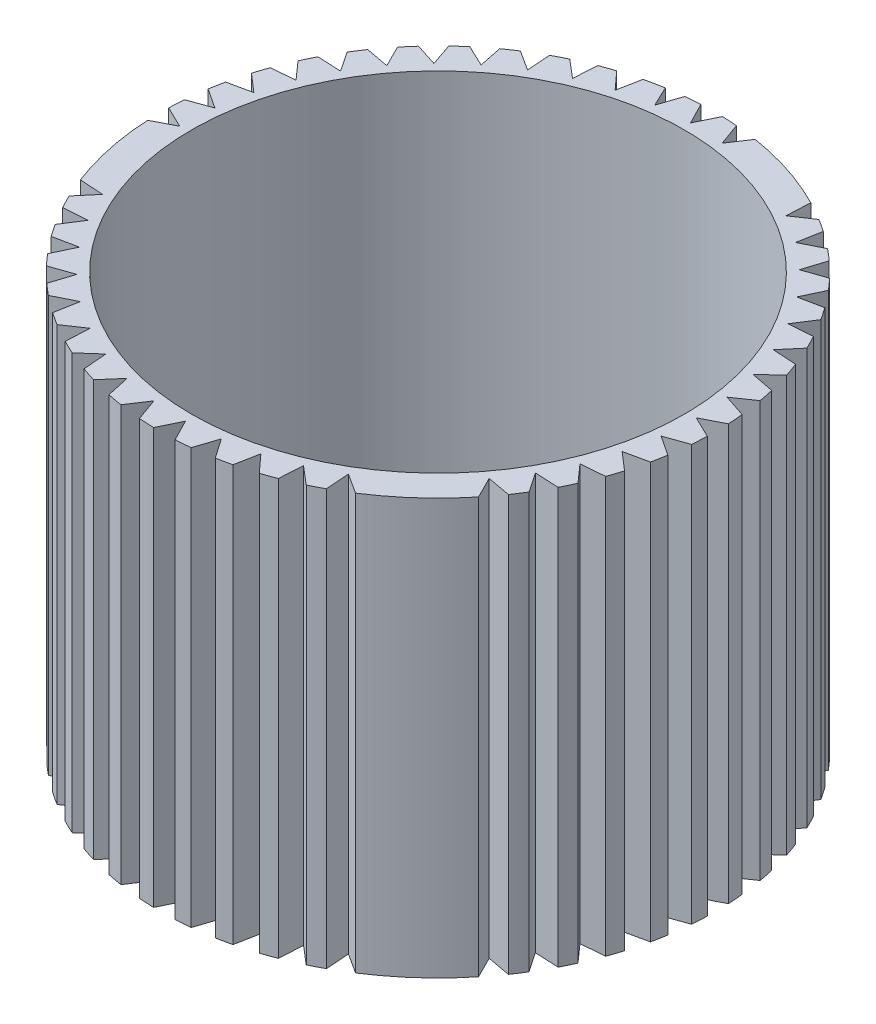
SolidWorks part; units mm, degrees
material "VeroWhite Plus"
ref_plane "Front Plane" through (0, 0, 0) normal (0, 0, 1) x (1, 0, 0)
ref_plane "Top Plane" through (0, 0, 0) normal (0, 1, 0) x (1, 0, 0)
ref_plane "Right Plane" through (0, 0, 0) normal (1, 0, 0) x (0, 0, -1)
sketch "Sketch1" plane through (0, 0, 0) normal (0, 1, 0) x (1, 0, 0)
  line L0 (9.9132, 31.394) -> (7.112, 32.1446) construction
  line L1 (11.113, 31.0725) -> (5.9121, 32.4661) construction
  line L2 (8.5126, 31.7693) -> (0, 0) construction
  line L3 (0, 0) -> (-6.2397, 29.8549) construction
  line L4 (0, 0) -> (-5.194, 30.0545) construction
  line L5 (0, 0) -> (-4.3196, 30.1926) construction
  line L6 (-4.9343, 30.0982) -> (-4.1426, 28.9552) construction
  line L7 (-4.1426, 28.9552) -> (-3.7032, 30.2744) construction
  line L8 (5.9121, 32.4661) -> (4.002, 25.3375) construction
  line L9 (11.113, 31.0725) -> (9.4356, 24.8123) construction
  line L10 (-32.4661, -5.9121) -> (-31.0725, -11.113) construction
  line L11 (-32.1446, -7.112) -> (-31.394, -9.9131) construction
  line L12 (22.2314, -24.282) -> (24.282, -22.2314) construction
  line L13 (-31.7693, -8.5126) -> (0, 0) construction
  line L14 (0, 0) -> (23.2567, -23.2567) construction
  line L15 (25.1604, -21.3531) -> (18.9649, -15.1575) construction
  line L16 (21.3531, -25.1604) -> (14.6891, -18.4964) construction
  line L17 (-32.4661, -5.9121) -> (-24.142, -3.6817) construction
  line L18 (-31.0725, -11.113) -> (-21.737, -8.6116) construction
  line L19 (-0.9635, 30.4848) -> (-0.3278, 29.2482) construction
  line L20 (-0.3278, 29.2482) -> (0.2801, 30.4987) construction
  line L21 (3.0238, 30.3497) -> (3.4927, 29.0407) construction
  line L22 (3.4927, 29.0407) -> (4.2586, 30.2012) construction
  line L23 (14.408, 26.8823) -> (14.3402, 25.4935) construction
  line L24 (14.3402, 25.4935) -> (15.4919, 26.2726) construction
  line L25 (17.7936, 24.7717) -> (17.5451, 23.4037) construction
  line L26 (17.5451, 23.4037) -> (18.7887, 24.0257) construction
  line L27 (20.8747, 22.2373) -> (20.4498, 20.9133) construction
  line L28 (20.4498, 20.9133) -> (21.7639, 21.3678) construction
  line L29 (23.5987, 19.3223) -> (23.0046, 18.0652) construction
  line L30 (23.0046, 18.0652) -> (24.3668, 18.3442) construction
  line L31 (25.9189, 16.0768) -> (25.1658, 14.9079) construction
  line L32 (25.1658, 14.9079) -> (26.5527, 15.0068) construction
  line L33 (27.7956, 12.5562) -> (26.8964, 11.4956) construction
  line L34 (26.8964, 11.4956) -> (28.2843, 11.4126) construction
  line L35 (29.1967, 8.8207) -> (28.1667, 7.8866) construction
  line L36 (28.1667, 7.8866) -> (29.532, 7.6231) construction
  line L37 (30.0982, 4.9343) -> (28.9552, 4.1426) construction
  line L38 (28.9552, 4.1426) -> (30.2744, 3.7032) construction
  line L39 (30.4848, 0.9635) -> (29.2482, 0.3278) construction
  line L40 (29.2482, 0.3278) -> (30.4987, -0.2801) construction
  line L41 (30.3497, -3.0238) -> (29.0407, -3.4927) construction
  line L42 (29.0407, -3.4927) -> (30.2012, -4.2586) construction
  line L43 (29.6954, -6.9594) -> (28.3364, -7.2534) construction
  line L44 (28.3364, -7.2534) -> (29.387, -8.1642) construction
  line L45 (28.533, -10.7759) -> (27.1472, -10.89) construction
  line L46 (27.1472, -10.89) -> (28.07, -11.9301) construction
  line L47 (26.8823, -14.408) -> (25.4935, -14.3402) construction
  line L48 (25.4935, -14.3402) -> (26.2726, -15.4919) construction
  line L49 (24.7717, -17.7936) -> (23.4037, -17.5451) construction
  line L50 (23.4037, -17.5451) -> (24.0257, -18.7887) construction
  line L51 (16.0768, -25.9188) -> (14.9079, -25.1658) construction
  line L52 (14.9079, -25.1658) -> (15.0068, -26.5527) construction
  line L53 (12.5562, -27.7955) -> (11.4956, -26.8963) construction
  line L54 (11.4956, -26.8963) -> (11.4126, -28.2843) construction
  line L55 (8.8207, -29.1967) -> (7.8866, -28.1667) construction
  line L56 (7.8866, -28.1667) -> (7.6231, -29.532) construction
  line L57 (4.9343, -30.0982) -> (4.1426, -28.9552) construction
  line L58 (4.1426, -28.9552) -> (3.7032, -30.2743) construction
  line L59 (0.9635, -30.4848) -> (0.3278, -29.2482) construction
  line L60 (0.3278, -29.2482) -> (-0.2801, -30.4987) construction
  line L61 (-3.0238, -30.3497) -> (-3.4927, -29.0407) construction
  line L62 (-3.4927, -29.0407) -> (-4.2586, -30.2012) construction
  line L63 (-6.9594, -29.6954) -> (-7.2534, -28.3364) construction
  line L64 (-7.2534, -28.3364) -> (-8.1642, -29.387) construction
  line L65 (-10.7759, -28.533) -> (-10.89, -27.1472) construction
  line L66 (-10.89, -27.1472) -> (-11.9301, -28.0699) construction
  line L67 (-14.408, -26.8823) -> (-14.3402, -25.4935) construction
  line L68 (-14.3402, -25.4935) -> (-15.4919, -26.2726) construction
  line L69 (-17.7936, -24.7717) -> (-17.5451, -23.4037) construction
  line L70 (-17.5451, -23.4037) -> (-18.7886, -24.0257) construction
  line L71 (-20.8747, -22.2373) -> (-20.4498, -20.9133) construction
  line L72 (-20.4498, -20.9133) -> (-21.7639, -21.3678) construction
  line L73 (-23.5987, -19.3223) -> (-23.0046, -18.0652) construction
  line L74 (-23.0046, -18.0652) -> (-24.3668, -18.3442) construction
  line L75 (-25.9188, -16.0768) -> (-25.1658, -14.9079) construction
  line L76 (-25.1658, -14.9079) -> (-26.5527, -15.0068) construction
  line L77 (-27.7955, -12.5562) -> (-26.8963, -11.4956) construction
  line L78 (-26.8963, -11.4956) -> (-28.2843, -11.4126) construction
  line L79 (-30.4848, -0.9635) -> (-29.2482, -0.3278) construction
  line L80 (-29.2482, -0.3278) -> (-30.4987, 0.2801) construction
  line L81 (-30.3497, 3.0238) -> (-29.0407, 3.4927) construction
  line L82 (-29.0407, 3.4927) -> (-30.2012, 4.2586) construction
  line L83 (-29.6954, 6.9594) -> (-28.3364, 7.2534) construction
  line L84 (-28.3364, 7.2534) -> (-29.387, 8.1642) construction
  line L85 (-28.533, 10.7759) -> (-27.1472, 10.89) construction
  line L86 (-27.1472, 10.89) -> (-28.0699, 11.9301) construction
  line L87 (-26.8823, 14.408) -> (-25.4935, 14.3402) construction
  line L88 (-25.4935, 14.3402) -> (-26.2726, 15.4919) construction
  line L89 (-24.7717, 17.7936) -> (-23.4037, 17.5451) construction
  line L90 (-23.4037, 17.5451) -> (-24.0257, 18.7887) construction
  line L91 (-22.2373, 20.8747) -> (-20.9133, 20.4498) construction
  line L92 (-20.9133, 20.4498) -> (-21.3678, 21.7639) construction
  line L93 (-19.3223, 23.5987) -> (-18.0652, 23.0046) construction
  line L94 (-18.0652, 23.0046) -> (-18.3442, 24.3668) construction
  line L95 (-16.0768, 25.9189) -> (-14.9079, 25.1658) construction
  line L96 (-14.9079, 25.1658) -> (-15.0068, 26.5527) construction
  line L97 (-12.5562, 27.7956) -> (-11.4956, 26.8964) construction
  line L98 (-11.4956, 26.8964) -> (-11.4126, 28.2843) construction
  line L99 (-8.8207, 29.1967) -> (-7.8866, 28.1667) construction
  line L100 (-7.8866, 28.1667) -> (-7.6231, 29.532) construction
  line L101 (-3.9843, 27.8484) -> (-3.1555, 30.3363)
  line L102 (-1.5142, 30.4624) -> (-0.3152, 28.1302)
  line L103 (-0.3152, 28.1302) -> (0.8312, 30.4887)
  line L104 (2.4749, 30.3994) -> (3.3592, 27.9307)
  line L105 (3.3592, 27.9307) -> (4.8036, 30.1194)
  line L106 (13.9199, 27.1383) -> (13.7921, 24.5191)
  line L107 (13.7921, 24.5191) -> (15.9641, 25.9884)
  line L108 (17.3431, 25.0892) -> (16.8745, 22.5091)
  line L109 (16.8745, 22.5091) -> (19.2197, 23.6823)
  line L110 (20.4695, 22.6109) -> (19.6682, 20.114)
  line L111 (19.6682, 20.114) -> (22.1465, 20.971)
  line L112 (23.2457, 19.7456) -> (22.1253, 17.3747)
  line L113 (22.1253, 17.3747) -> (24.6943, 17.9009)
  line L114 (25.6241, 16.5425) -> (24.2039, 14.3381)
  line L115 (24.2039, 14.3381) -> (26.8195, 14.5245)
  line L116 (27.5641, 13.0564) -> (25.8683, 11.0562)
  line L117 (25.8683, 11.0562) -> (28.4859, 10.8996)
  line L118 (29.0325, 9.3468) -> (27.0901, 7.5851)
  line L119 (27.0901, 7.5851) -> (29.6649, 7.0882)
  line L120 (30.0041, 5.4774) -> (27.8484, 3.9843)
  line L121 (27.8484, 3.9843) -> (30.3363, 3.1555)
  line L122 (30.4624, 1.5142) -> (28.1302, 0.3152)
  line L123 (28.1302, 0.3152) -> (30.4887, -0.8312)
  line L124 (30.3994, -2.4749) -> (27.9307, -3.3592)
  line L125 (27.9307, -3.3592) -> (30.1194, -4.8036)
  line L126 (29.8163, -6.4217) -> (27.2533, -6.9761)
  line L127 (27.2533, -6.9761) -> (29.2347, -8.6939)
  line L128 (28.723, -10.2585) -> (26.1096, -10.4737)
  line L129 (26.1096, -10.4737) -> (27.8498, -12.4354)
  line L130 (27.1383, -13.9199) -> (24.5191, -13.7921)
  line L131 (24.5191, -13.7921) -> (25.9884, -15.9641)
  line L132 (25.0892, -17.343) -> (22.5091, -16.8745)
  line L133 (22.5091, -16.8745) -> (23.6823, -19.2197)
  line L134 (16.5425, -25.6241) -> (14.3381, -24.2038)
  line L135 (14.3381, -24.2038) -> (14.5245, -26.8195)
  line L136 (13.0564, -27.5641) -> (11.0562, -25.8683)
  line L137 (11.0562, -25.8683) -> (10.8996, -28.4859)
  line L138 (9.3468, -29.0325) -> (7.5851, -27.0901)
  line L139 (7.5851, -27.0901) -> (7.0882, -29.6649)
  line L140 (5.4774, -30.0041) -> (3.9843, -27.8484)
  line L141 (3.9843, -27.8484) -> (3.1555, -30.3363)
  line L142 (1.5142, -30.4624) -> (0.3152, -28.1302)
  line L143 (0.3152, -28.1302) -> (-0.8311, -30.4887)
  line L144 (-2.4749, -30.3994) -> (-3.3592, -27.9307)
  line L145 (-3.3592, -27.9307) -> (-4.8036, -30.1193)
  line L146 (-6.4217, -29.8163) -> (-6.9761, -27.2533)
  line L147 (-6.9761, -27.2533) -> (-8.6939, -29.2347)
  line L148 (-10.2585, -28.723) -> (-10.4737, -26.1095)
  line L149 (-10.4737, -26.1095) -> (-12.4354, -27.8498)
  line L150 (-13.9199, -27.1383) -> (-13.7921, -24.5191)
  line L151 (-13.7921, -24.5191) -> (-15.9641, -25.9884)
  line L152 (-17.343, -25.0892) -> (-16.8745, -22.5091)
  line L153 (-16.8745, -22.5091) -> (-19.2197, -23.6823)
  line L154 (-20.4695, -22.6108) -> (-19.6681, -20.114)
  line L155 (-19.6681, -20.114) -> (-22.1465, -20.971)
  line L156 (-23.2457, -19.7456) -> (-22.1253, -17.3747)
  line L157 (-22.1253, -17.3747) -> (-24.6943, -17.9009)
  line L158 (-25.6241, -16.5425) -> (-24.2038, -14.3381)
  line L159 (-24.2038, -14.3381) -> (-26.8195, -14.5245)
  line L160 (-27.5641, -13.0564) -> (-25.8683, -11.0562)
  line L161 (-25.8683, -11.0562) -> (-28.4859, -10.8996)
  line L162 (-30.4624, -1.5142) -> (-28.1302, -0.3152)
  line L163 (-28.1302, -0.3152) -> (-30.4887, 0.8312)
  line L164 (-30.3994, 2.4749) -> (-27.9307, 3.3592)
  line L165 (-27.9307, 3.3592) -> (-30.1193, 4.8036)
  line L166 (-29.8163, 6.4217) -> (-27.2533, 6.9761)
  line L167 (-27.2533, 6.9761) -> (-29.2347, 8.6939)
  line L168 (-28.723, 10.2585) -> (-26.1095, 10.4737)
  line L169 (-26.1095, 10.4737) -> (-27.8498, 12.4354)
  line L170 (-27.1383, 13.9199) -> (-24.5191, 13.7921)
  line L171 (-24.5191, 13.7921) -> (-25.9884, 15.9641)
  line L172 (-25.0892, 17.343) -> (-22.5091, 16.8745)
  line L173 (-22.5091, 16.8745) -> (-23.6823, 19.2197)
  line L174 (-22.6108, 20.4695) -> (-20.114, 19.6682)
  line L175 (-20.114, 19.6682) -> (-20.971, 22.1465)
  line L176 (-19.7456, 23.2457) -> (-17.3747, 22.1253)
  line L177 (-17.3747, 22.1253) -> (-17.9009, 24.6943)
  line L178 (-16.5425, 25.6241) -> (-14.3381, 24.2039)
  line L179 (-14.3381, 24.2039) -> (-14.5245, 26.8195)
  line L180 (-13.0564, 27.5641) -> (-11.0562, 25.8683)
  line L181 (-11.0562, 25.8683) -> (-10.8996, 28.4859)
  line L182 (-9.3468, 29.0325) -> (-7.5851, 27.0901)
  line L183 (-7.5851, 27.0901) -> (-7.0882, 29.6649)
  line L184 (-5.0434, 30.0801) -> (-3.9843, 27.8484)
  arc A0 (21.3531, -25.1604) -> (25.1604, -21.3531) centre (0, 0) ccw construction
  arc A1 (-10.2585, -28.723) -> (-8.6939, -29.2347) centre (0, 0) ccw
  arc A2 (-6.4217, -29.8163) -> (-4.8036, -30.1193) centre (0, 0) ccw
  arc A3 (-13.9199, -27.1383) -> (-12.4354, -27.8498) centre (0, 0) ccw
  arc A4 (-17.343, -25.0892) -> (-15.9641, -25.9884) centre (0, 0) ccw
  arc A5 (-20.4695, -22.6108) -> (-19.2197, -23.6823) centre (0, 0) ccw
  arc A6 (-23.2457, -19.7456) -> (-22.1465, -20.971) centre (0, 0) ccw
  arc A7 (-25.6241, -16.5425) -> (-24.6943, -17.9009) centre (0, 0) ccw
  arc A8 (-27.5641, -13.0564) -> (-26.8195, -14.5245) centre (0, 0) ccw
  arc A9 (-2.4749, -30.3994) -> (-0.8311, -30.4887) centre (0, 0) ccw
  arc A10 (1.5142, -30.4624) -> (3.1555, -30.3363) centre (0, 0) ccw
  arc A11 (5.4774, -30.0041) -> (7.0882, -29.6649) centre (0, 0) ccw
  arc A12 (9.3468, -29.0325) -> (10.8996, -28.4859) centre (0, 0) ccw
  arc A13 (13.0564, -27.5641) -> (14.5245, -26.8195) centre (0, 0) ccw
  arc A14 (16.5425, -25.6241) -> (23.6823, -19.2197) centre (0, 0) ccw
  arc A15 (25.0892, -17.343) -> (25.9884, -15.9641) centre (0, 0) ccw
  arc A16 (28.723, -10.2585) -> (29.2347, -8.6939) centre (0, 0) ccw
  arc A17 (27.1383, -13.9199) -> (27.8498, -12.4354) centre (0, 0) ccw
  arc A18 (29.8163, -6.4217) -> (30.1194, -4.8036) centre (0, 0) ccw
  arc A19 (30.3994, -2.4749) -> (30.4887, -0.8312) centre (0, 0) ccw
  arc A20 (30.4624, 1.5142) -> (30.3363, 3.1555) centre (0, 0) ccw
  arc A21 (30.0041, 5.4774) -> (29.6649, 7.0882) centre (0, 0) ccw
  arc A22 (29.0325, 9.3468) -> (28.4859, 10.8996) centre (0, 0) ccw
  arc A23 (27.5641, 13.0564) -> (26.8195, 14.5245) centre (0, 0) ccw
  arc A24 (25.6241, 16.5425) -> (24.6943, 17.9009) centre (0, 0) ccw
  arc A25 (23.2457, 19.7456) -> (22.1465, 20.971) centre (0, 0) ccw
  arc A26 (20.4695, 22.6109) -> (19.2197, 23.6823) centre (0, 0) ccw
  arc A27 (13.9199, 27.1383) -> (4.8036, 30.1194) centre (0, 0) ccw
  arc A28 (17.3431, 25.0892) -> (15.9641, 25.9884) centre (0, 0) ccw
  arc A29 (2.4749, 30.3994) -> (0.8312, 30.4887) centre (0, 0) ccw
  arc A30 (-1.5142, 30.4624) -> (-3.1555, 30.3363) centre (0, 0) ccw
  arc A31 (-5.0434, 30.0801) -> (-7.0882, 29.6649) centre (0, 0) ccw
  arc A32 (-9.3468, 29.0325) -> (-10.8996, 28.4859) centre (0, 0) ccw
  arc A33 (-13.0564, 27.5641) -> (-14.5245, 26.8195) centre (0, 0) ccw
  arc A34 (-16.5425, 25.6241) -> (-17.9009, 24.6943) centre (0, 0) ccw
  arc A35 (-19.7456, 23.2457) -> (-20.971, 22.1465) centre (0, 0) ccw
  arc A36 (-22.6108, 20.4695) -> (-23.6823, 19.2197) centre (0, 0) ccw
  arc A37 (-25.0892, 17.343) -> (-25.9884, 15.9641) centre (0, 0) ccw
  arc A38 (-27.1383, 13.9199) -> (-27.8498, 12.4354) centre (0, 0) ccw
  arc A39 (-28.723, 10.2585) -> (-29.2347, 8.6939) centre (0, 0) ccw
  arc A40 (-29.8163, 6.4217) -> (-30.1193, 4.8036) centre (0, 0) ccw
  arc A41 (-30.3994, 2.4749) -> (-30.4887, 0.8312) centre (0, 0) ccw
  arc A42 (-30.4624, -1.5142) -> (-28.4859, -10.8996) centre (0, 0) ccw
  circle A43 centre (0, 0) radius 28.132 construction
  circle A44 centre (0, 0) radius 27.132
  dimension "D1" = 26.805
  dimension "D2" = 2
  dimension "D3" = 1
extrude "Boss-Extrude1" add sketch "Sketch1" along normal blind 45.77
